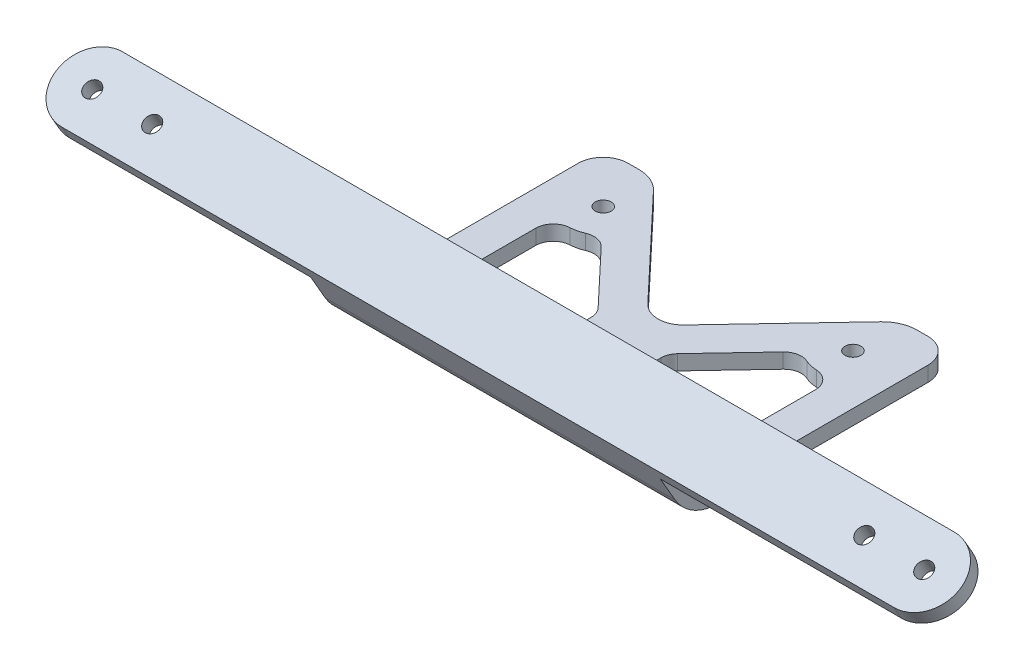
SolidWorks part; units mm, degrees
ref_plane "前视基准面" through (0, 0, 0) normal (0, 0, 1) x (1, 0, 0)
ref_plane "上视基准面" through (0, 0, 0) normal (0, 1, 0) x (1, 0, 0)
ref_plane "右视基准面" through (0, 0, 0) normal (1, 0, 0) x (0, 0, -1)
sketch "草图1" plane through (0, 0, 0) normal (0, 1, 0) x (1, 0, 0)
  line L1 (0, 0) -> (70, 0)
  line L2 (0, 0) -> (0, 50)
  line L3 (0, 50) -> (70, 50)
  line L4 (70, 0) -> (70, 50)
  dimension "D1" = 70
  dimension "D2" = 50
extrude "凸台-拉伸1" add sketch "草图1" along normal blind 3
sketch "草图2" plane through (0, 0, 0) normal (-1, 0, 0) x (0, 0, 1)
  line L0 (0, 15) -> (-6.0622, 18.5)
  line L1 (0, 0) -> (4, 0)
  line L2 (0, 0) -> (0, 15)
  line L4 (4, 0) -> (4, 15)
  line L5 (-6.0622, 18.5) -> (-4.5622, 21.0981)
  line L6 (-4.5622, 21.0981) -> (4, 16.1547)
  line L7 (4, 16.1547) -> (4, 15)
  dimension "D1" = 15
  dimension "D2" = 4
  dimension "D3" = 7
  dimension "D4" = 120
  dimension "D5" = 3
extrude "凸台-拉伸2" add sketch "草图2" against normal up to surface (70 mm away) up to face at (70, 1.5, -25)
sketch "草图3" plane through (0, 13.8481, 7.9952) normal (0, 0.866, 0.5) x (1, 0, 0)
  line L0 (-36.265, 4.6132) -> (106.265, 4.6132) construction
  line L1 (35, 44.8013) -> (35, 4.6132) construction
  line L2 (70, 44.8013) -> (0, 44.8013) construction
  line L3 (-48.265, 4.6132) -> (-36.265, 4.6132) construction
  line L4 (-48.265, 11.6132) -> (-36.265, 11.6132)
  line L5 (-48.265, -2.3868) -> (-36.265, -2.3868)
  line L6 (106.265, 4.6132) -> (118.265, 4.6132) construction
  line L7 (106.265, 11.6132) -> (118.265, 11.6132)
  line L8 (106.265, -2.3868) -> (118.265, -2.3868)
  line L9 (-36.265, 11.6132) -> (106.265, 11.6132)
  line L10 (-36.265, -2.3868) -> (106.265, -2.3868)
  circle A0 centre (-36.265, 4.6132) radius 1.6
  circle A1 centre (106.265, 4.6132) radius 1.6
  circle A2 centre (-48.265, 4.6132) radius 1.6
  circle A3 centre (118.265, 4.6132) radius 1.6
  arc A4 (-48.265, 11.6132) -> (-48.265, -2.3868) centre (-48.265, 4.6132) ccw
  arc A7 (118.265, -2.3868) -> (118.265, 11.6132) centre (118.265, 4.6132) ccw
  point P13 (-42.265, 4.6132)
  point P18 (112.265, 4.6132)
  dimension "D2" = 3.2
  dimension "D3" = 3.2
  dimension "D6" = 7
  dimension "D1" = 142.53
  dimension "D4" = 12
  dimension "D5" = 12
  dimension "D7" = 14
extrude "凸台-拉伸3" add sketch "草图3" against normal up to surface (3 mm away) up to face at (35, 16.75, -3.0311)
sketch "草图4" plane through (0, 11.25, 6.4952) normal (0, -0.866, -0.5) x (1, 0, 0)
  line L0 (-48.265, 2.3868) -> (118.265, 2.3868) construction
  line L1 (70, -2.8812) -> (0, -2.8812)
  line L2 (70, -2.8812) -> (70, 2.3868)
  line L3 (70, 2.3868) -> (0, 2.3868)
  line L4 (0, -2.8812) -> (0, 2.3868)
extrude "凸台-拉伸4" add sketch "草图4" along normal up to surface up to face at (35, 6.3453, 4)
fillet "圆角1" radius 5 1 edges at (35, 3, 0)
sketch "草图5" plane through (0, -1.1934, 2.067) normal (0, -0.5, 0.866) x (1, 0, 0)
  line L1 (0, 3.866) -> (70, 3.866)
  line L2 (0, 3.866) -> (0, -25)
  line L3 (0, -25) -> (70, -25)
  line L4 (70, 3.866) -> (70, -25)
extrude "切除-拉伸1" cut sketch "草图5" along normal through all
sketch "草图6" plane through (0, 5.8066, -10.0574) normal (0, 0.5, -0.866) x (-1, 0, 0)
  line L1 (-70, 15.9904) -> (0, 15.9904)
  line L2 (-70, 15.9904) -> (-70, 12.9904)
  line L3 (-70, 12.9904) -> (0, 12.9904)
  line L4 (0, 15.9904) -> (0, 12.9904)
extrude "切除-拉伸2" cut sketch "草图6" along normal through all
fillet "圆角2" radius 5 2 edges at (0, 1.5, -50) (70, 1.5, -50)
sketch "草图7" plane through (0, 3, 0) normal (0, 1, 0) x (1, 0, 0)
  line L0 (35, 50) -> (35, 3.5622) construction
  line L1 (65, 50) -> (5, 50) construction
  line L2 (118.265, 3.5622) -> (-48.265, 3.5622) construction
  circle A0 centre (10, 40) radius 1.6
  circle A1 centre (60, 40) radius 1.6
  circle A2 centre (35, 10) radius 1.6
  dimension "D1" = 3.2
  dimension "D2" = 40
  dimension "D3" = 50
  dimension "D4" = 10
ref_plane "基准面1" through (0, 13.8481, 7.9952) normal (0, 0.866, 0.5) x (1, 0, 0)
extrude "切除-拉伸3" cut sketch "草图7" against normal blind 10
sketch "草图8" plane through (0, 3, 0) normal (0, 1, 0) x (1, 0, 0)
  line L0 (35, 10) -> (35, 50) construction
  line L1 (65, 50) -> (5, 50) construction
  line L2 (12.2577, 47.8054) -> (31.3643, 27.5675)
  line L3 (38.6357, 27.5675) -> (57.7423, 47.8054)
  line L4 (5, 50) -> (7.1677, 50)
  line L5 (62.8323, 50) -> (65, 50)
  line L6 (7.1677, 50) -> (62.8323, 50)
  circle A0 centre (10, 40) radius 1.6 construction
  arc A1 (31.3643, 27.5675) -> (38.6357, 27.5675) centre (35, 31) ccw
  arc A2 (12.2577, 47.8054) -> (7.1677, 50) centre (7.1677, 43) ccw
  arc A3 (57.7423, 47.8054) -> (62.8323, 50) centre (62.8323, 43) cw
  point P21 (59.8142, 50)
  line M5 (65, 50) -> (5, 50)
  dimension "D3" = 10
  dimension "D4" = 7
  dimension "D5" = 7
  dimension "D1" = 7
  dimension "D2" = 21
extrude "切除-拉伸4" cut sketch "草图8" against normal blind 10 contours A1 L0 L6 A2 L2 | L0 A1 L3 A3 M5
sketch "草图9" plane through (0, 3, 0) normal (0, 1, 0) x (1, 0, 0)
  line L0 (7, 29.5119) -> (7, 12)
  line L2 (0, 45) -> (0, 5) construction
  line L3 (42.955, 21.9458) -> (53.2041, 32.8017)
  line L4 (42, 12) -> (42, 19.5431)
  line L5 (59.5, 8.5) -> (45.5, 8.5)
  line L6 (63, 29.5119) -> (63, 12)
  line L13 (10.5, 8.5) -> (24.5, 8.5)
  line L14 (28, 12) -> (28, 19.5431)
  line L15 (27.045, 21.9458) -> (16.7959, 32.8017)
  line L16 (35, 26) -> (35, 2.0622) construction
  line L17 (118.265, 2.0622) -> (-48.265, 2.0622) construction
  line L18 (12.2577, 47.8054) -> (31.3643, 27.5675) construction
  line L20 (0, 5) -> (70, 5) construction
  arc A0 (31.3643, 27.5675) -> (38.6357, 27.5675) centre (35, 31) ccw construction
  arc A2 (10.3333, 33.0079) -> (7, 29.5119) centre (10.5, 29.5119) ccw
  arc A3 (16.7959, 32.8017) -> (12.834, 33.5993) centre (14.2509, 30.399) ccw
  arc A4 (10.3333, 33.0079) -> (12.834, 33.5993) centre (10, 40) ccw
  arc A5 (27.045, 21.9458) -> (28, 19.5431) centre (24.5, 19.5431) cw
  arc A6 (24.5, 8.5) -> (28, 12) centre (24.5, 12) ccw
  arc A7 (10.5, 8.5) -> (7, 12) centre (10.5, 12) cw
  arc A8 (59.5, 8.5) -> (63, 12) centre (59.5, 12) ccw
  arc A9 (45.5, 8.5) -> (42, 12) centre (45.5, 12) cw
  arc A10 (42.955, 21.9458) -> (42, 19.5431) centre (45.5, 19.5431) ccw
  arc A11 (59.6667, 33.0079) -> (57.166, 33.5993) centre (60, 40) cw
  arc A12 (53.2041, 32.8017) -> (57.166, 33.5993) centre (55.7491, 30.399) cw
  arc A13 (59.6667, 33.0079) -> (63, 29.5119) centre (59.5, 29.5119) cw
  dimension "D5" = 7
  dimension "D6" = 7
  dimension "D7" = 3.5
  dimension "D8" = 3.5
  dimension "D9" = 3.5
  dimension "D10" = 3.5
  dimension "D1" = 7
  dimension "D2" = 7
  dimension "D3" = 7
  dimension "D4" = 3.5
extrude "切除-拉伸5" cut sketch "草图9" against normal through all
fillet "圆角4" radius 10 1 edges at (35, 0, 2.756)
